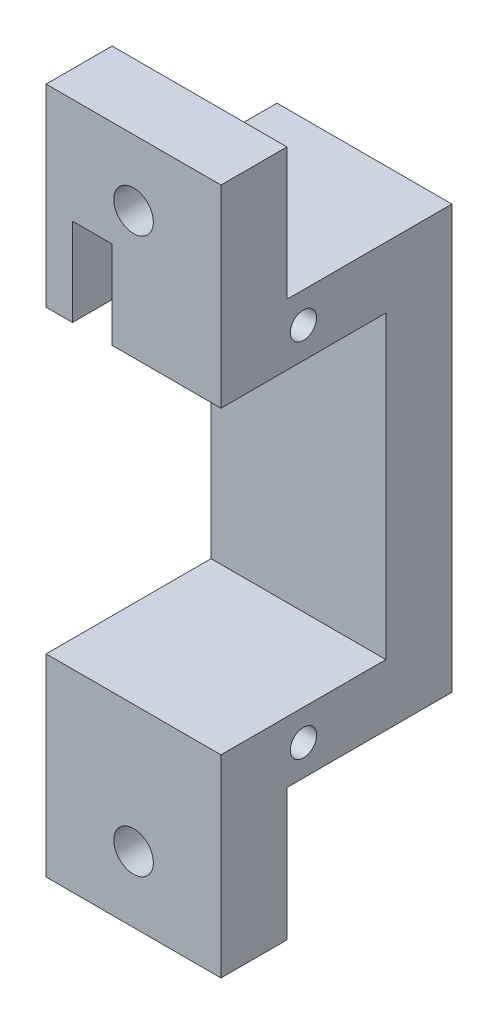
SolidWorks part; units mm, degrees
material "ABS"
ref_plane "Plano frontal" through (0, 0, 0) normal (0, 0, 1) x (1, 0, 0)
ref_plane "Plano superior" through (0, 0, 0) normal (0, 1, 0) x (1, 0, 0)
ref_plane "Plano direito" through (0, 0, 0) normal (1, 0, 0) x (0, 0, -1)
sketch "Esboço1" plane through (0, 0, 0) normal (0, 1, 0) x (1, 0, 0)
  line L1 (-21.7379, -6.1618) -> (-8.4879, -6.1618)
  line L2 (-21.7379, -6.1618) -> (-21.7379, -18.6618)
  line L3 (-21.7379, -18.6618) -> (-8.4879, -18.6618)
  line L4 (-8.4879, -6.1618) -> (-8.4879, -18.6618)
extrude "Ressalto-extrusão1" add sketch "Esboço1" against normal blind 4.65
sketch "Esboço2" plane through (0, 0, 6.1618) normal (0, 0, -1) x (-1, 0, 0)
  line L1 (21.7379, 0) -> (8.4879, 0)
  line L2 (21.7379, 0) -> (21.7379, -32.05)
  line L3 (21.7379, -32.05) -> (8.4879, -32.05)
  line L4 (8.4879, 0) -> (8.4879, -32.05)
extrude "Ressalto-extrusão2" add sketch "Esboço2" along normal blind 5
sketch "Esboço3" plane through (0, 0, 6.1618) normal (0, 0, 1) x (1, 0, 0)
  line L0 (-21.7379, -32.05) -> (-21.7379, -4.65) construction
  line L1 (-8.4879, -32.05) -> (-21.7379, -32.05)
  line L2 (-8.4879, -32.05) -> (-8.4879, -27.4)
  line L3 (-8.4879, -27.4) -> (-21.7379, -27.4)
  line L4 (-21.7379, -32.05) -> (-21.7379, -27.4)
extrude "Ressalto-extrusão3" add sketch "Esboço3" along normal blind 12.5
sketch "Esboço4" plane through (0, -32.05, 0) normal (0, -1, 0) x (-1, 0, 0)
  line L0 (8.4879, -1.1618) -> (8.4879, -18.6618) construction
  line L1 (21.7379, -18.6618) -> (8.4879, -18.6618)
  line L2 (21.7379, -18.6618) -> (21.7379, -13.6618)
  line L3 (21.7379, -13.6618) -> (8.4879, -13.6618)
  line L4 (8.4879, -18.6618) -> (8.4879, -13.6618)
extrude "Ressalto-extrusão4" add sketch "Esboço4" along normal blind 10
sketch "Esboço5" plane through (0, 0, 0) normal (0, 1, 0) x (1, 0, 0)
  line L0 (-8.4879, -18.6618) -> (-8.4879, -1.1618) construction
  line L1 (-21.7379, -18.6618) -> (-8.4879, -18.6618)
  line L2 (-21.7379, -18.6618) -> (-21.7379, -13.6618)
  line L3 (-21.7379, -13.6618) -> (-8.4879, -13.6618)
  line L4 (-8.4879, -18.6618) -> (-8.4879, -13.6618)
extrude "Ressalto-extrusão5" add sketch "Esboço5" along normal blind 10
sketch "Esboço6" plane through (0, 0, 13.6618) normal (0, 0, -1) x (-1, 0, 0)
  line L0 (8.4879, 10) -> (21.7379, 10) construction
  line L1 (21.7379, 10) -> (21.7379, 0) construction
  line L2 (21.7379, -42.05) -> (8.4879, -42.05) construction
  line L3 (21.7379, -42.05) -> (21.7379, -32.05) construction
  circle A0 centre (15.1129, 5) radius 1.5
  circle A1 centre (15.1129, -37.05) radius 1.5
  point P10 (15.1129, -42.05)
  point P13 (21.7379, -37.05)
  dimension "D1" = 5
  dimension "D2" = 6.625
  dimension "D3" = 5
  dimension "D4" = 6.625
extrude "Corte-extrusão1" cut sketch "Esboço6" against normal blind 10
sketch "Esboço7" plane through (-8.4879, 0, 0) normal (1, 0, 0) x (0, 0, -1)
  line L0 (-18.6618, -4.65) -> (-18.6618, 10) construction
  line L1 (-13.6618, 0) -> (-1.1618, 0) construction
  circle A0 centre (-12.4118, -2.325) radius 1
  dimension "D1" = 6.25
  dimension "D2" = 2.325
sketch "Esboço8" plane through (-8.4879, 0, 0) normal (1, 0, 0) x (0, 0, -1)
  line L0 (-18.6618, -42.05) -> (-18.6618, -27.4) construction
  line L1 (-1.1618, -32.05) -> (-13.6618, -32.05) construction
  circle A0 centre (-12.4118, -29.725) radius 1
  dimension "D1" = 6.25
  dimension "D2" = 2.325
extrude "Corte-extrusão2" cut sketch "Esboço7" against normal through all
extrude "Corte-extrusão3" cut sketch "Esboço8" against normal through all
sketch "Esboço9" plane through (0, 0, 0) normal (0, 1, 0) x (1, 0, 0)
  line L1 (-19.7379, -18.6618) -> (-16.7379, -18.6618)
  line L2 (-19.7379, -18.6618) -> (-19.7379, -8.2708)
  line L3 (-19.7379, -8.2708) -> (-16.7379, -8.2708)
  line L4 (-16.7379, -18.6618) -> (-16.7379, -8.2708)
  line L5 (-21.7379, -1.1618) -> (-21.7379, -13.6618) construction
  line L7 (-21.7379, -18.6618) -> (-8.4879, -18.6618) construction
  dimension "D1" = 2
  dimension "D2" = 3
  dimension "D3" = 0
extrude "Corte-extrusão4" cut sketch "Esboço9" against normal blind 10
sketch "Esboço10" plane through (0, 0, 13.6618) normal (0, 0, -1) x (-1, 0, 0)
  line L1 (19.7379, 0) -> (16.7379, 0)
  line L2 (19.7379, 0) -> (19.7379, 2)
  line L3 (19.7379, 2) -> (16.7379, 2)
  line L4 (16.7379, 0) -> (16.7379, 2)
  dimension "D2" = 2
extrude "Corte-extrusão5" cut sketch "Esboço10" against normal blind 10
